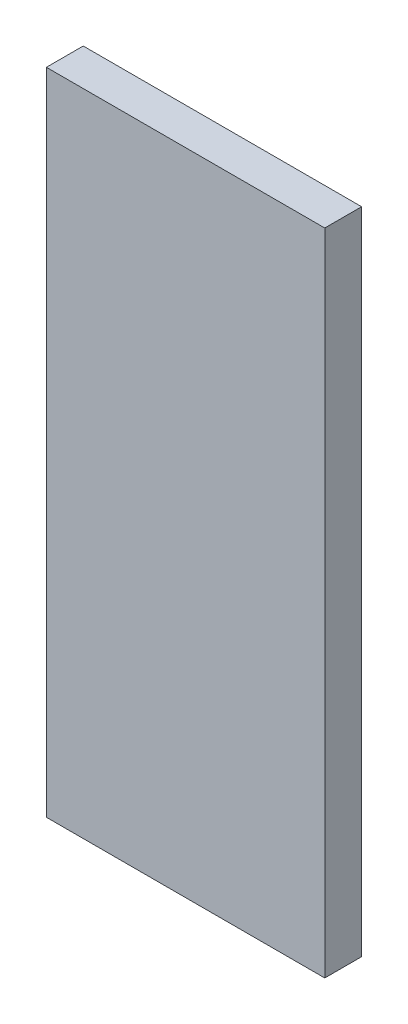
SolidWorks part; units mm, degrees
ref_plane "Front Plane" through (0, 0, 0) normal (0, 0, 1) x (1, 0, 0)
ref_plane "Top Plane" through (0, 0, 0) normal (0, 1, 0) x (1, 0, 0)
ref_plane "Right Plane" through (0, 0, 0) normal (1, 0, 0) x (0, 0, -1)
sketch "Sketch1" plane through (0, 0, 0) normal (0, 0, 1) x (1, 0, 0)
  line L1 (-7.5534, -17.6249) -> (7.5534, -17.6249)
  line L2 (-7.5534, -17.6249) -> (-7.5534, 17.6249)
  line L3 (-7.5534, 17.6249) -> (7.5534, 17.6249)
  line L4 (7.5534, -17.6249) -> (7.5534, 17.6249)
  line L5 (-7.5534, -17.6249) -> (7.5534, 17.6249) construction
  line L6 (-7.5534, 17.6249) -> (7.5534, -17.6249) construction
  point P0 (0, 0)
extrude "Boss-Extrude1" add sketch "Sketch1" along normal blind 2
sketch "Sketch2" plane through (0, 0, 0) normal (0, 0, -1) x (-1, 0, 0)
  circle A0 centre (0, 10.5416) radius 1.8801
  circle A1 centre (0, 0) radius 2.1352
extrude "Boss-Extrude2" add sketch "Sketch2" along normal blind 3
fillet "Fillet1" radius 1.5 2 edges at (-2.1352, 0, -3) (-1.8801, 10.5416, -3)
